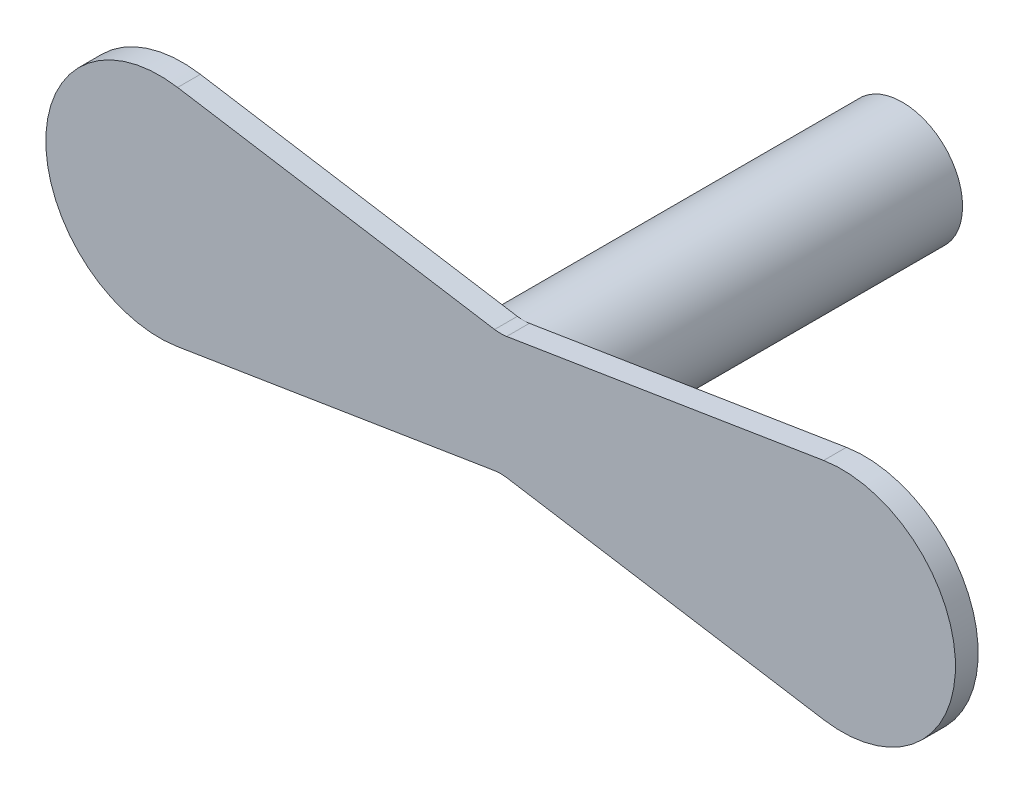
SolidWorks part; units mm, degrees
ref_plane "Front Plane" through (0, 0, 0) normal (0, 0, 1) x (1, 0, 0)
ref_plane "Top Plane" through (0, 0, 0) normal (0, 1, 0) x (1, 0, 0)
ref_plane "Right Plane" through (0, 0, 0) normal (1, 0, 0) x (0, 0, -1)
sketch "Sketch1" plane through (0, 0, 0) normal (0, 0, 1) x (1, 0, 0)
  circle A0 centre (0, 0) radius 7.9375
  dimension "D1" = 15.875
extrude "Boss-Extrude1" add sketch "Sketch1" along normal blind 50
sketch "Sketch2" plane through (0, 0, 50) normal (0, 0, 1) x (1, 0, 0)
  line L0 (0, -7.9375) -> (0, 7.9375)
  line L1 (0, 7.9375) -> (42.6121, 14.8087)
  line L2 (0, -7.9375) -> (42.6121, -14.8087)
  line L3 (0, 0) -> (45, 0) construction
  arc A0 (42.6121, 14.8087) -> (42.6121, -14.8087) centre (45, 0) cw
  circle A1 centre (0, 0) radius 7.9375 construction
  point P4 (0, 0)
  point P9 (0, 2.1103)
  point P10 (0, 1.2338)
  point P11 (0, 1.5)
  point P12 (0, 7.9375)
  point P15 (30.3495, 6.9967)
  dimension "D1" = 15
  dimension "D2" = 45
extrude "Boss-Extrude2" add sketch "Sketch2" along normal blind 3
mirror "Mirror1" about plane through (0, -7.9375, 53) normal (1, 0, 0) of "Boss-Extrude2"
fillet "Fillet1" radius 5 2 edges at (0, -7.9375, 51.5) (0, 7.9375, 51.5)
